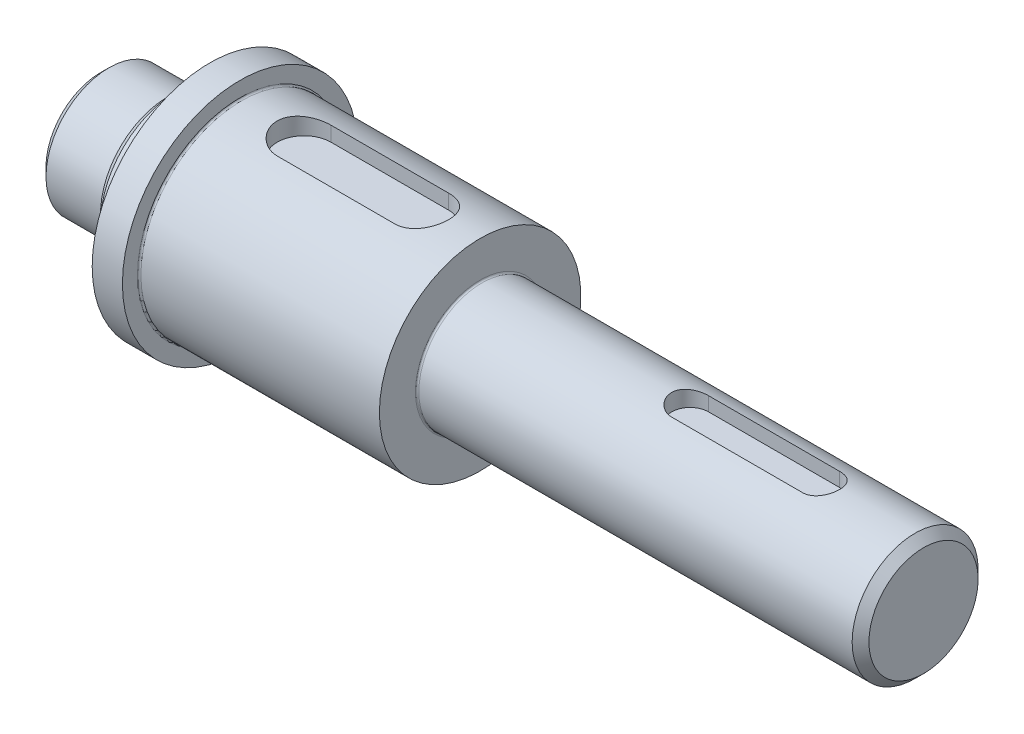
SolidWorks part; units mm, degrees
material "普通碳钢"
ref_plane "前视" through (0, 0, 0) normal (0, 0, 1) x (1, 0, 0)
ref_plane "上视" through (0, 0, 0) normal (0, 1, 0) x (1, 0, 0)
ref_plane "右视" through (0, 0, 0) normal (1, 0, 0) x (0, 0, -1)
sketch "草图1" plane through (0, 0, 0) normal (0, 0, 1) x (1, 0, 0)
  line L0 (-105.2812, 0) -> (107.7107, 0) construction
  line L1 (-152.7883, 0) -> (-152.7883, 37.5)
  line L2 (-152.7883, 37.5) -> (-112.7883, 37.5)
  line L3 (-112.7883, 37.5) -> (-112.7883, 45)
  line L4 (-112.7883, 45) -> (-87.7883, 45)
  line L5 (-87.7883, 45) -> (-87.7883, 70)
  line L6 (-69.7883, 60) -> (73.2117, 60)
  line L7 (73.2117, 60) -> (73.2117, 37.5)
  line L10 (73.2117, 37.5) -> (337.2117, 37.5)
  line L11 (337.2117, 37.5) -> (337.2117, 0)
  line L12 (337.2117, 0) -> (-152.7883, 0)
  line L13 (-87.7883, 70) -> (-69.7883, 70)
  line L14 (-69.7883, 60) -> (-69.7883, 70)
  dimension "D1" = 37.5
  dimension "D2" = 60
  dimension "D3" = 45
  dimension "D4" = 40
  dimension "D5" = 37.5
  dimension "D6" = 490
  dimension "D7" = 143
  dimension "D9" = 70
  dimension "D10" = 25
  dimension "D11" = 18
revolve "旋转1" add sketch "草图1" angle 360 about L0
ref_plane "基准面1" through (0, 60, 0) normal (0, 1, 0) x (-1, 0, 0)
sketch "草图2" plane through (0, 60, 0) normal (0, 1, 0) x (-1, 0, 0)
  line L0 (80.578, 0) -> (-294.3785, 0) construction
  line L1 (-38.2117, 15.8328) -> (31.7883, 15.8328)
  line L2 (31.7883, -16.1672) -> (-38.2117, -16.1672)
  line L4 (-73.2117, 60) -> (-73.2117, -60) construction
  arc A0 (31.7883, 15.8328) -> (31.7883, -16.1672) centre (31.7883, -0.1672) cw
  arc A1 (-38.2117, 15.8328) -> (-38.2117, -16.1672) centre (-38.2117, -0.1672) ccw
  dimension "D2" = 16
  dimension "D3" = 35
  dimension "D1" = 70
extrude "切除-拉伸1" cut sketch "草图2" against normal blind 11
ref_plane "基准面2" through (0, 28.5, 0) normal (0, 1, 0) x (-1, 0, 0)
sketch "草图3" plane through (0, 28.5, 0) normal (0, 1, 0) x (-1, 0, 0)
  line L0 (-238.0643, 0) -> (-429.1049, 0) construction
  line L1 (-337.2117, 37.5) -> (-337.2117, -37.5) construction
  line L2 (-198.2117, 11) -> (-276.2117, 11)
  line L5 (-198.2117, -11.0317) -> (-276.2117, -11.0317)
  arc A0 (-276.2117, 11) -> (-276.2117, -11.0317) centre (-276.2117, -0.0159) ccw
  arc A1 (-198.2117, 11) -> (-198.2117, -11.0317) centre (-198.2117, -0.0159) cw
  dimension "D3" = 11.0159
  dimension "D2" = 11.0159
  dimension "D1" = 78
  dimension "D4" = 61
extrude "切除-拉伸2" cut sketch "草图3" against normal blind 1 and the other way through all
chamfer "倒角1" distance 5 angle 45 3 edges at (337.2117, 0, 37.5) (-112.7883, 0, 45) (-152.7883, 0, 37.5)
fillet "圆角1" radius 1 3 edges at (-87.7883, 0, 45) (73.2117, 0, 37.5) (-69.7883, 0, 60)
